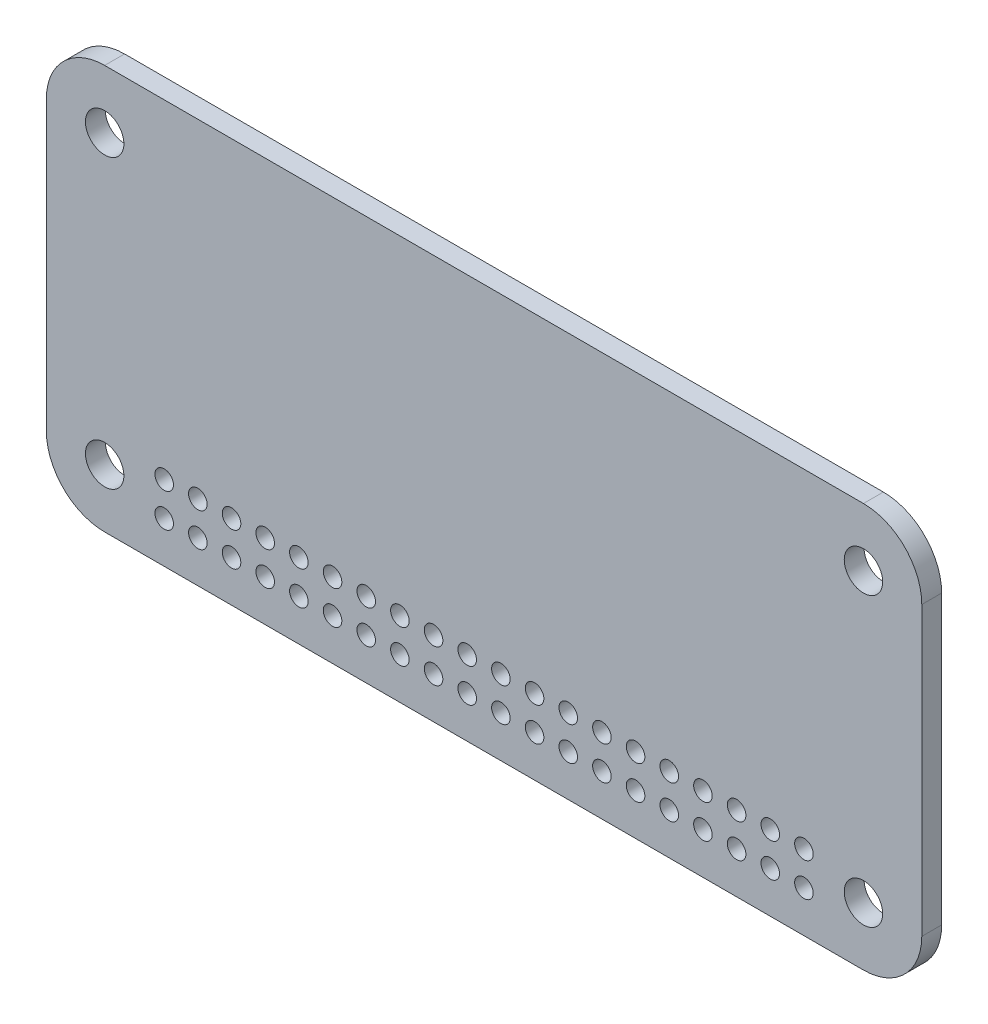
SolidWorks part; units mm, degrees
ref_plane "Alzado" through (0, 0, 0) normal (0, 0, 1) x (1, 0, 0)
ref_plane "Planta" through (0, 0, 0) normal (0, 1, 0) x (1, 0, 0)
ref_plane "Vista lateral" through (0, 0, 0) normal (1, 0, 0) x (0, 0, -1)
sketch "Croquis1" plane through (0, 0, 0) normal (0, 0, 1) x (1, 0, 0)
  line L0 (0, 15.24) -> (0, -15.24) construction
  line L1 (28.62, -15.24) -> (-28.62, -15.24)
  line L2 (33.02, -10.84) -> (33.02, 10.84)
  line L3 (28.62, 15.24) -> (-28.62, 15.24)
  line L4 (-33.02, -10.84) -> (-33.02, 10.84)
  line L5 (33.02, -15.24) -> (-33.02, 15.24) construction
  line L6 (33.02, 15.24) -> (-33.02, -15.24) construction
  line L7 (-33.02, 0) -> (33.02, 0) construction
  line L8 (-28.62, -10.84) -> (28.62, -10.84) construction
  line L9 (-24.13, -12.11) -> (-24.13, -9.57) construction
  line L10 (-24.13, -9.57) -> (-21.59, -9.57) construction
  line L11 (-24.13, -9.57) -> (24.13, -9.57) construction
  arc A0 (33.02, 10.84) -> (28.62, 15.24) centre (28.62, 10.84) ccw
  arc A1 (28.62, -15.24) -> (33.02, -10.84) centre (28.62, -10.84) ccw
  arc A2 (-28.62, -15.24) -> (-33.02, -10.84) centre (-28.62, -10.84) cw
  arc A3 (-28.62, 15.24) -> (-33.02, 10.84) centre (-28.62, 10.84) ccw
  circle A4 centre (-28.62, 10.84) radius 1.45
  circle A5 centre (28.62, 10.84) radius 1.45
  circle A6 centre (28.62, -10.84) radius 1.45
  circle A7 centre (-28.62, -10.84) radius 1.45
  circle A8 centre (-24.13, -9.57) radius 0.7
  circle A9 centre (-24.13, -12.11) radius 0.7
  circle A10 centre (-21.59, -9.57) radius 0.7
  circle A11 centre (-21.59, -12.11) radius 0.7
  circle A12 centre (-19.05, -9.57) radius 0.7
  circle A13 centre (-19.05, -12.11) radius 0.7
  circle A14 centre (-16.51, -9.57) radius 0.7
  circle A15 centre (-16.51, -12.11) radius 0.7
  circle A16 centre (-13.97, -9.57) radius 0.7
  circle A17 centre (-13.97, -12.11) radius 0.7
  circle A18 centre (-11.43, -9.57) radius 0.7
  circle A19 centre (-11.43, -12.11) radius 0.7
  circle A20 centre (-8.89, -9.57) radius 0.7
  circle A21 centre (-8.89, -12.11) radius 0.7
  circle A22 centre (-6.35, -9.57) radius 0.7
  circle A23 centre (-6.35, -12.11) radius 0.7
  circle A24 centre (-3.81, -9.57) radius 0.7
  circle A25 centre (-3.81, -12.11) radius 0.7
  circle A26 centre (-1.27, -9.57) radius 0.7
  circle A27 centre (-1.27, -12.11) radius 0.7
  circle A28 centre (1.27, -9.57) radius 0.7
  circle A29 centre (1.27, -12.11) radius 0.7
  circle A30 centre (3.81, -9.57) radius 0.7
  circle A31 centre (3.81, -12.11) radius 0.7
  circle A32 centre (6.35, -9.57) radius 0.7
  circle A33 centre (6.35, -12.11) radius 0.7
  circle A34 centre (8.89, -9.57) radius 0.7
  circle A35 centre (8.89, -12.11) radius 0.7
  circle A36 centre (11.43, -9.57) radius 0.7
  circle A37 centre (11.43, -12.11) radius 0.7
  circle A38 centre (13.97, -9.57) radius 0.7
  circle A39 centre (13.97, -12.11) radius 0.7
  circle A40 centre (16.51, -9.57) radius 0.7
  circle A41 centre (16.51, -12.11) radius 0.7
  circle A42 centre (19.05, -9.57) radius 0.7
  circle A43 centre (19.05, -12.11) radius 0.7
  circle A44 centre (21.59, -9.57) radius 0.7
  circle A45 centre (21.59, -12.11) radius 0.7
  circle A46 centre (24.13, -9.57) radius 0.7
  circle A47 centre (24.13, -12.11) radius 0.7
  point P0 (0, 0)
  point P29 (-24.13, -10.84)
  point P31 (0, -9.57)
  dimension "D3" = 4.4
  dimension "D4" = 2.9
  dimension "D6" = 1.4
  dimension "D1" = 66.04
  dimension "D2" = 30.48
  dimension "D5" = 2.54
  dimension "D8" = 2.54
  dimension "D7" = 20
extrude "Saliente-Extruir1" add sketch "Croquis1" along normal blind 1.5
